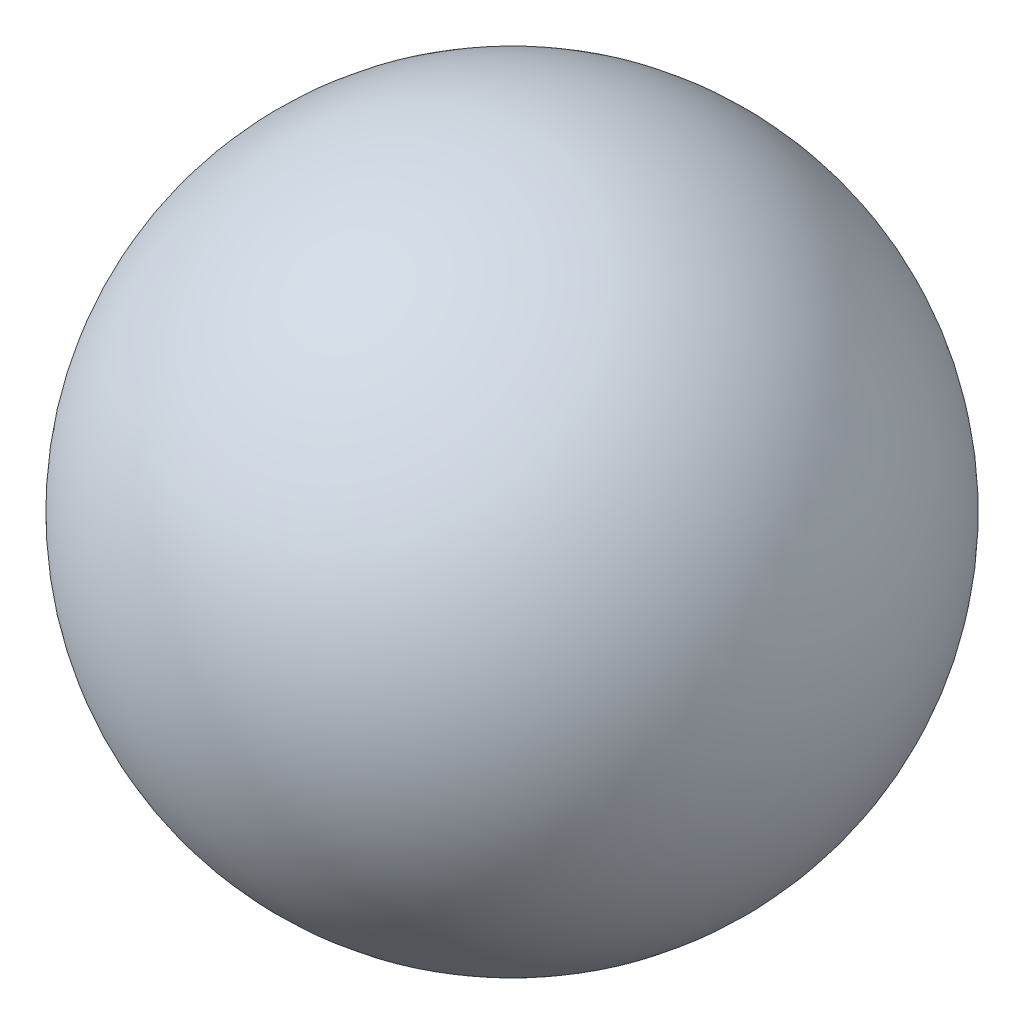
SolidWorks part; units mm, degrees
material "Massless"
ref_plane "Front Plane" through (0, 0, 0) normal (0, 0, 1) x (1, 0, 0)
ref_plane "Top Plane" through (0, 0, 0) normal (0, 1, 0) x (1, 0, 0)
ref_plane "Right Plane" through (0, 0, 0) normal (1, 0, 0) x (0, 0, -1)
sketch "Sketch2" plane through (0, 0, 0) normal (0, 0, 1) x (1, 0, 0)
  line L0 (0, 88.9) -> (0, -88.9) construction
  circle A0 centre (0, 0) radius 88.9
  dimension "D1" = 177.8
revolve "Revolve4" add sketch "Sketch2" angle 360 about L0
